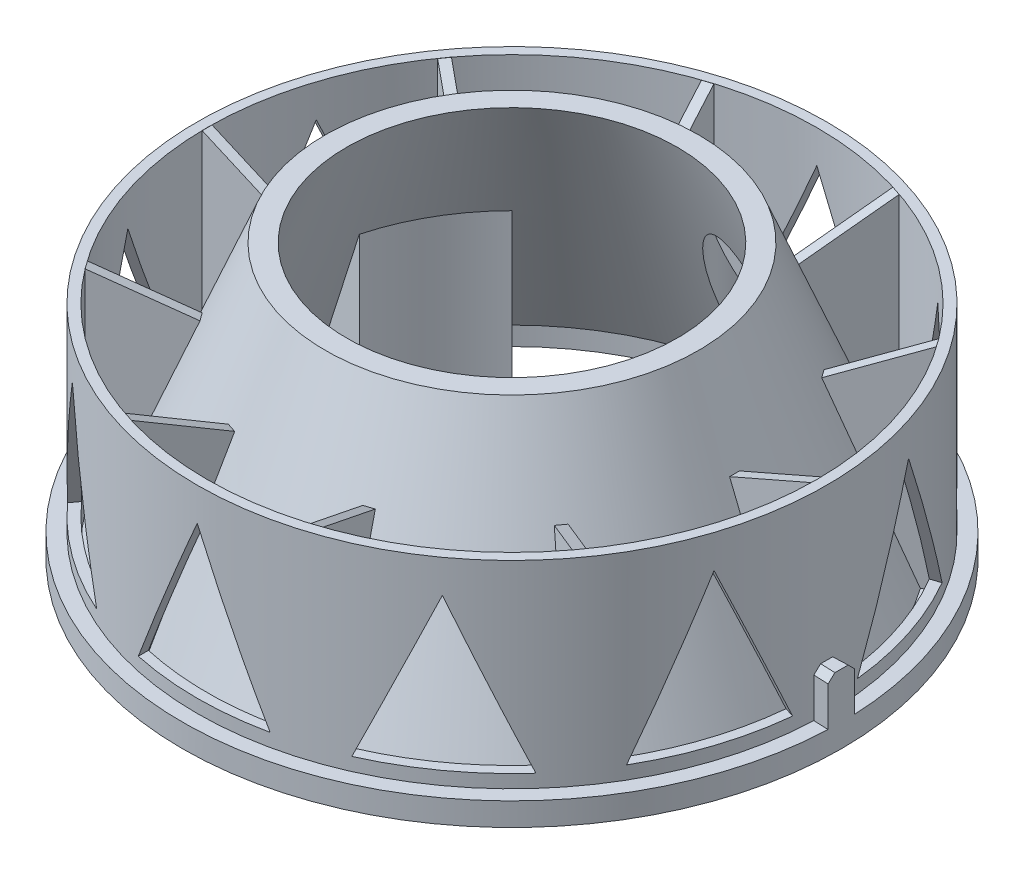
SolidWorks part; units mm, degrees
material "ABS"
ref_plane "Спереди" through (0, 0, 0) normal (0, 0, 1) x (1, 0, 0)
ref_plane "Сверху" through (0, 0, 0) normal (0, 1, 0) x (1, 0, 0)
ref_plane "Справа" through (0, 0, 0) normal (1, 0, 0) x (0, 0, -1)
sketch "Эскиз1" plane through (0, 0, 0) normal (0, 0, 1) x (1, 0, 0)
  line L0 (0, 0) -> (0, 41.0099) construction
  line L1 (46.25, 35) -> (47.75, 35)
  line L2 (46.25, 3) -> (46.25, 35)
  line L3 (50, 0) -> (50, 5)
  line L4 (50, 5) -> (47.75, 5)
  line L5 (47.75, 5) -> (47.75, 35)
  line L6 (41.25, 3) -> (25.089, 43)
  line L7 (46.25, 3) -> (44.4856, 3)
  line L8 (-48, 3) -> (48, 3) construction
  line L9 (50, 0) -> (32.75, 0)
  line L10 (32.75, 0) -> (32.75, 3)
  line L11 (44.4856, 3) -> (28.3246, 43)
  line L12 (25.089, 43) -> (28.3246, 43)
  line L13 (-33, 17.6237) -> (33, 17.6237) construction
  line L14 (32.75, 3) -> (-29.5829, 3) construction
  line L17 (41.25, 3) -> (32.75, 3)
  circle A0 centre (0, 17.6237) radius 33 construction
  dimension "D5" = 3
  dimension "D8" = 68
  dimension "D9" = 66
  dimension "D1" = 50
  dimension "D2" = 2.25
  dimension "D3" = 1.5
  dimension "D4" = 5
  dimension "D6" = 30
  dimension "D7" = 8.5
  dimension "D10" = 40
  dimension "D11" = 17.25
  dimension "D12" = 32.75
revolve "Повернуть1" add sketch "Эскиз1" angle 360 about L0
sketch "Эскиз2" plane through (0, 0, 0) normal (0, 0, 1) x (1, 0, 0)
  line L0 (46.3265, 35) -> (33.755, 29.5084)
  line L1 (47.75, 35) -> (-47.75, 35) construction
  line L2 (33.755, 29.5084) -> (44.4256, 2.3778)
  line L3 (44.4256, 2.3778) -> (46.3265, 2.3778)
  line L4 (46.3265, 2.3778) -> (46.3265, 35)
extrude "Ребро" add sketch "Эскиз2" along normal mid plane 1.5
pattern_circular "Массив ребер" count 10 over 360 about axis through (0, 0, 0) along (0, 1, 0) of "Ребро"
sketch "Эскиз3" plane through (0, 0, 0) normal (0, 1, 0) x (1, 0, 0)
  line L1 (0, 0) -> (0, 41.0716) construction
  circle A0 centre (0, 36) radius 5
  circle A3 centre (0, 0) radius 36 construction
  dimension "D1" = 10
  dimension "D2" = 72
extrude "Вырез под РМО" cut sketch "Эскиз3" against normal blind 24.5 and the other way blind 37.9
sketch "Эскиз4" plane through (0, 0, 0) normal (0, 1, 0) x (1, 0, 0)
  line L0 (0, 0) -> (-25, 43.3013) construction
  line L1 (0, 0) -> (-29.3449, 29.3449)
  line L2 (0, 0) -> (-63.5782, 0) construction
  line L3 (-10.741, 40.0859) -> (0, 0)
  circle A0 centre (0, 0) radius 50 construction
  arc A1 (-29.3449, 29.3449) -> (-10.741, 40.0859) centre (0, 0) cw
  point P8 (-20.75, 35.9401)
  dimension "D1" = 41.5
  dimension "D2" = 30
  dimension "60" = 60
extrude "Вырез под РД" cut sketch "Эскиз4" along normal up to surface (3 mm away) up to face at (0, 3, -4.125)
pattern_circular "Круговой массив2" count 6 over 360 about axis through (0, 0, 0) along (0, 1, 0) of "Вырез под РД"
sketch "Эскиз5" plane through (0, 0, 0) normal (0, 0, 1) x (1, 0, 0)
  line L0 (-10, 7) -> (0, 30)
  line L1 (-10, 7) -> (10, 7)
  line L2 (-10, 7) -> (-10, 30) construction
  line L3 (-10, 30) -> (10, 30) construction
  line L4 (10, 7) -> (10, 30) construction
  line L5 (-10, 7) -> (10, 30) construction
  line L6 (-10, 30) -> (10, 7) construction
  line L7 (0, 30) -> (10, 7)
  line L8 (50, 5) -> (-50, 5) construction
  line L9 (47.75, 35) -> (-47.75, 35) construction
  point P0 (0, 18.5)
  dimension "D1" = 5
  dimension "D2" = 20
  dimension "D3" = 2
extrude "Вырез-Вытянуть1" cut sketch "Эскиз5" along normal up to surface (1.5352 mm away) from surface
pattern_circular "Круговой массив3" count 10 over 360 about axis through (0, 0, 0) along (0, 1, 0) of "Вырез-Вытянуть1"
sketch "Эскиз7" plane through (0, 5, 0) normal (0, 1, 0) x (1, 0, 0)
  line L0 (0, 0) -> (50, 0) construction
  line L1 (47.7118, 1.91) -> (49.96, 2)
  line L2 (47.7118, -1.91) -> (49.96, -2)
  circle A0 centre (0, 0) radius 47.75 construction
  circle A1 centre (0, 0) radius 50
  circle A2 centre (0, 0) radius 50
  circle A3 centre (0, 0) radius 47.75
  circle M5 centre (0, 0) radius 47.75
  circle M6 centre (0, 0) radius 50
  dimension "D2" = 4
  dimension "D1" = 0
extrude "Бобышка-Вытянуть1" add sketch "Эскиз7" along normal blind 7 contours L0 A2 L1 M5 | L0 A3 L2 M6
chamfer "Фаска1" distance 1 angle 45 2 edges at (48.8359, 12, 1.955) (48.8359, 12, -1.955)
sketch "Эскиз8" plane through (0, 0, 0) normal (0, -1, 0) x (1, 0, 0)
  circle A1 centre (0, 0) radius 45
  circle A2 centre (0, 0) radius 50 construction
  circle A3 centre (0, 0) radius 50
  dimension "D1" = 90
extrude "Вырез-Вытянуть2" cut sketch "Эскиз8" against normal blind 1.5
sketch "Эскиз9" plane through (0, 3, 0) normal (0, 1, 0) x (1, 0, 0)
  line L2 (31.6341, 8.4763) -> (39.8444, 10.6763)
  line L3 (29.1682, 29.1682) -> (23.1577, 23.1577)
  line L4 (31.6341, 8.4763) -> (39.8444, 10.6763)
  line L5 (29.1682, 29.1682) -> (23.1577, 23.1577)
  arc A2 (31.6341, 8.4763) -> (23.1577, 23.1577) centre (0, 0) ccw
  arc A3 (39.8444, 10.6763) -> (29.1682, 29.1682) centre (0, 0) ccw
  arc A4 (31.6341, 8.4763) -> (23.1577, 23.1577) centre (0, 0) ccw
  arc A5 (39.8444, 10.6763) -> (29.1682, 29.1682) centre (0, 0) ccw
  dimension "D1" = 0
extrude "Бобышка-Вытянуть2" add sketch "Эскиз9" along normal up to surface (21.0382 mm away)
pattern_circular "Круговой массив4" count 3 over 360 about axis through (0, 0, 0) along (0, -1, 0) of "Бобышка-Вытянуть2"
sketch "Эскиз10" plane through (0, 0, 0) normal (0, -1, 0) x (1, 0, 0)
  circle A0 centre (0, 0) radius 37.5
  circle A2 centre (0, 37.5) radius 2.2
  dimension "D1" = 75
  dimension "D2" = 4.4
extrude "Вырез-Вытянуть3" cut sketch "Эскиз10" against normal blind 12 contours A0 A2 | A0 A2
chamfer "Фаска2" distance 1 angle 45 1 edges at (0, 0, 35.3)
pattern_circular "Круговой массив5" count 3 over 360 about axis through (0, 0, 0) along (0, 1, 0) of "Вырез-Вытянуть3", "Фаска2"
